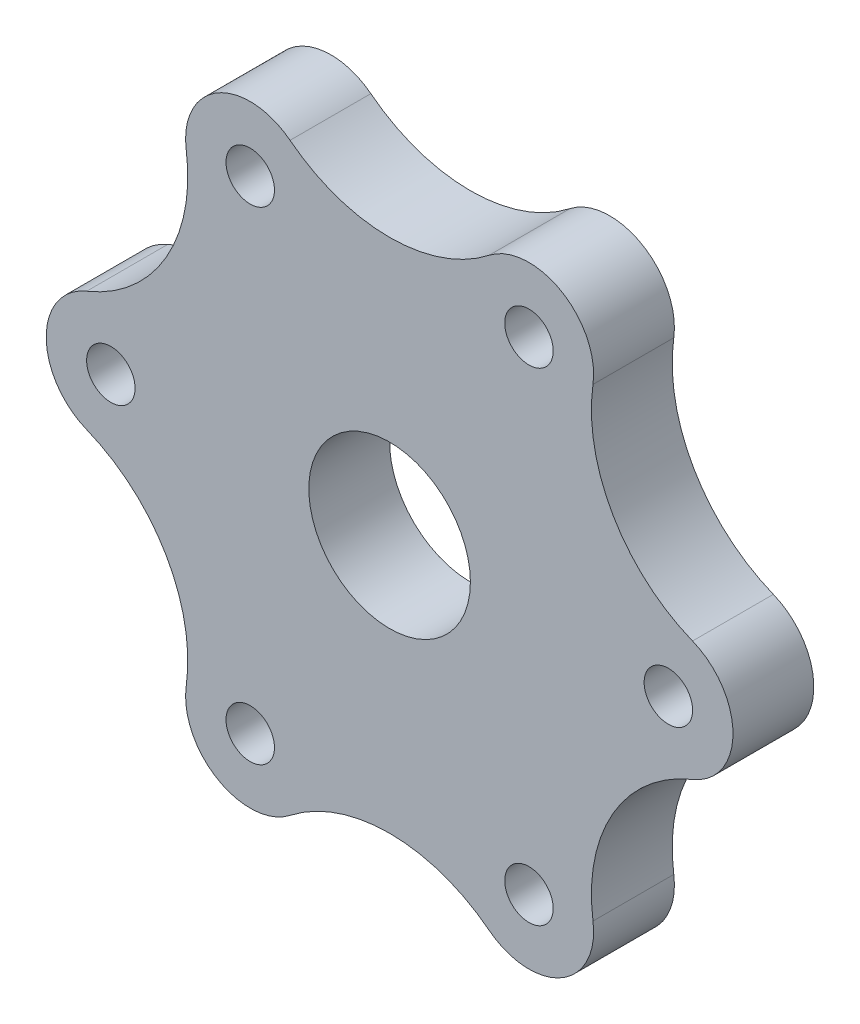
SolidWorks part; units mm, degrees
ref_plane "Front Plane" through (0, 0, 0) normal (0, 0, 1) x (1, 0, 0)
ref_plane "Top Plane" through (0, 0, 0) normal (0, 1, 0) x (1, 0, 0)
ref_plane "Right Plane" through (0, 0, 0) normal (1, 0, 0) x (0, 0, -1)
sketch "Sketch1" plane through (0, 0, 0) normal (0, 0, 1) x (1, 0, 0)
  circle A0 centre (0, 0) radius 10
  circle A1 centre (0, 0) radius 34.5 construction
  circle A2 centre (34.5, 0) radius 3
  arc A3 (37.493, -7.419) -> (37.493, 7.419) centre (34.5, 0) ccw
  circle A4 centre (17.25, -29.8779) radius 3
  arc A5 (12.3214, -36.1794) -> (25.1716, -28.7604) centre (17.25, -29.8779) ccw
  circle A6 centre (-17.25, -29.8779) radius 3
  arc A7 (-25.1716, -28.7604) -> (-12.3214, -36.1794) centre (-17.25, -29.8779) ccw
  circle A8 centre (-34.5, 0) radius 3
  arc A9 (-37.493, 7.419) -> (-37.493, -7.419) centre (-34.5, 0) ccw
  circle A10 centre (-17.25, 29.8779) radius 3
  arc A11 (-12.3214, 36.1794) -> (-25.1716, 28.7604) centre (-17.25, 29.8779) ccw
  circle A12 centre (17.25, 29.8779) radius 3
  arc A13 (25.1716, 28.7604) -> (12.3214, 36.1794) centre (17.25, 29.8779) ccw
  arc A14 (25.1716, 28.7604) -> (37.493, 7.419) centre (44.9755, 25.9666) ccw
  arc A15 (37.493, -7.419) -> (25.1716, -28.7604) centre (44.9755, -25.9666) ccw
  arc A16 (12.3214, -36.1794) -> (-12.3214, -36.1794) centre (0, -51.9332) ccw
  arc A17 (-25.1716, -28.7604) -> (-37.493, -7.419) centre (-44.9755, -25.9666) ccw
  arc A18 (-37.493, 7.419) -> (-25.1716, 28.7604) centre (-44.9755, 25.9666) ccw
  arc A19 (-12.3214, 36.1794) -> (12.3214, 36.1794) centre (0, 51.9332) ccw
  point P19 (0, 0)
  point P43 (0, 0)
  dimension "D1" = 20
  dimension "D2" = 69
  dimension "D3" = 6
  dimension "D4" = 16
  dimension "D6" = 20
  dimension "D5" = 6
  dimension "D7" = 6
extrude "Boss-Extrude1" add sketch "Sketch1" along normal mid plane 10
